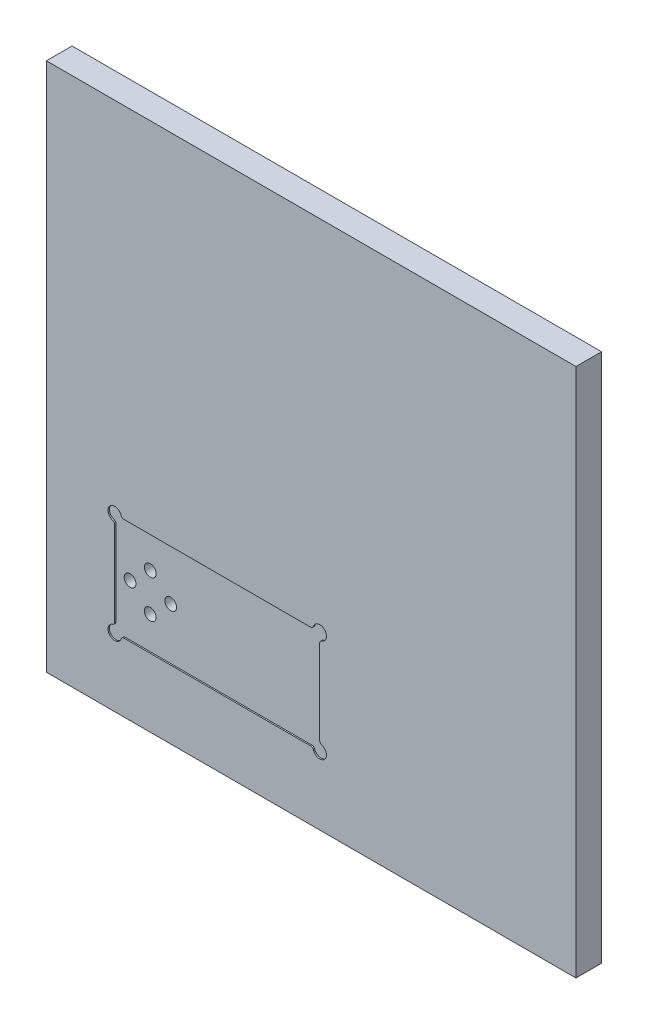
SolidWorks part; units mm, degrees
ref_plane "Front" through (0, 0, 0) normal (0, 0, 1) x (1, 0, 0)
ref_plane "Top" through (0, 0, 0) normal (0, 1, 0) x (1, 0, 0)
ref_plane "Right" through (0, 0, 0) normal (1, 0, 0) x (0, 0, -1)
sketch "Sketch1" plane through (0, 0, 0) normal (0, 0, 1) x (1, 0, 0)
  line L5 (0, 0) -> (393.7, 0)
  line L6 (0, 0) -> (0, 393.7)
  line L7 (0, 393.7) -> (393.7, 393.7)
  line L8 (393.7, 0) -> (393.7, 393.7)
  dimension "D1" = 393.7
extrude "Boss-Extrude1" add sketch "Sketch1" along normal blind 19.05
sketch "Sketch2" plane through (0, 0, 19.05) normal (0, 0, 1) x (1, 0, 0)
  line L0 (0, 0) -> (393.7, 0) construction
  line L1 (55.8, 50.8) -> (198.2, 50.8)
  line L2 (50.8, 55.8) -> (50.8, 122.254)
  line L3 (55.8, 127.254) -> (198.2, 127.254)
  line L4 (203.2, 55.8) -> (203.2, 122.254)
  line L5 (0, 393.7) -> (0, 0) construction
  arc A4 (203.2, 122.254) -> (198.2, 127.254) centre (203.2, 127.254) ccw
  arc A5 (198.2, 50.8) -> (203.2, 55.8) centre (203.2, 50.8) ccw
  arc A6 (50.8, 55.8) -> (55.8, 50.8) centre (50.8, 50.8) ccw
  arc A7 (55.8, 127.254) -> (50.8, 122.254) centre (50.8, 127.254) ccw
  point P10 (0, 0)
  point P17 (0, 0)
  point P18 (50.8, 50.8)
  point P19 (203.2, 50.8)
  dimension "D5" = 10
  dimension "D1" = 76.454
  dimension "D2" = 152.4
  dimension "D3" = 50.8
  dimension "D4" = 50.8
extrude "Cut-Extrude2" cut sketch "Sketch2" against normal blind 1
sketch "Sketch3" plane through (0, 0, 18.05) normal (0, 0, 1) x (1, 0, 0)
  line L1 (50.8, 50.8) -> (203.2, 50.8) construction
  line L2 (50.8, 50.8) -> (50.8, 127.254) construction
  line L3 (50.8, 127.254) -> (203.2, 127.254) construction
  line L4 (203.2, 50.8) -> (203.2, 127.254) construction
  line L6 (50.8, 122.254) -> (50.8, 55.8) construction
  line L7 (198.2, 127.254) -> (55.8, 127.254) construction
  circle A0 centre (61.2, 89.2) radius 4.3656
  circle A1 centre (91.4, 89.2) radius 4.3656
  circle A2 centre (76.2, 75) radius 4.3656
  circle A3 centre (76.2, 103.2) radius 4.3656
  dimension "D5" = 8.7312
  dimension "D1" = 76.454
  dimension "D2" = 152.4
  dimension "D6" = 10.4
  dimension "D7" = 38.4
  dimension "D8" = 40.6
  dimension "D9" = 24.2
  dimension "D10" = 25.4
  dimension "D11" = 52.4
extrude "Cut-Extrude4" cut sketch "Sketch3" against normal blind 12.5
fillet "Fillet1" radius 2 8 edges at (203.2, 122.254, 18.55) (198.2, 127.254, 18.55) (203.2, 55.8, 18.55) (198.2, 50.8, 18.55) (55.8, 50.8, 18.55) (50.8, 55.8, 18.55) (55.8, 127.254, 18.55) (50.8, 122.254, 18.55)
